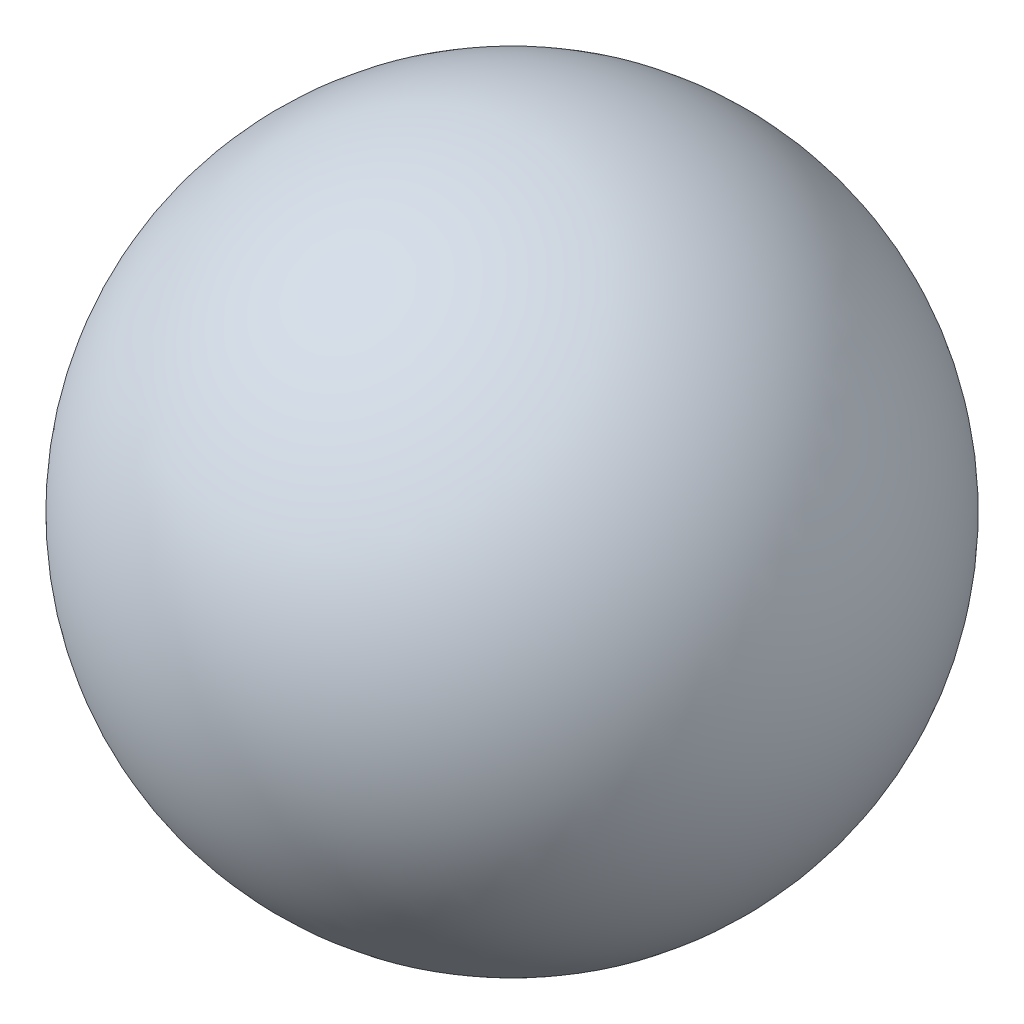
SolidWorks part; units mm, degrees
ref_plane "Plan de face" through (0, 0, 0) normal (0, 0, 1) x (1, 0, 0)
ref_plane "Plan de dessus" through (0, 0, 0) normal (0, 1, 0) x (1, 0, 0)
ref_plane "Plan de droite" through (0, 0, 0) normal (1, 0, 0) x (0, 0, -1)
sketch "Esquisse1" plane through (0, 0, 0) normal (0, 0, 1) x (1, 0, 0)
  line L0 (0, -11) -> (0, 0) construction
  line L1 (0, 0) -> (0, 11) construction
  line L2 (0, 11) -> (0, -11)
  arc A0 (0, 11) -> (0, -11) centre (0, 0) cw
  dimension "D1" = 11
revolve "Révolution1" add sketch "Esquisse1" angle 360 about L2
